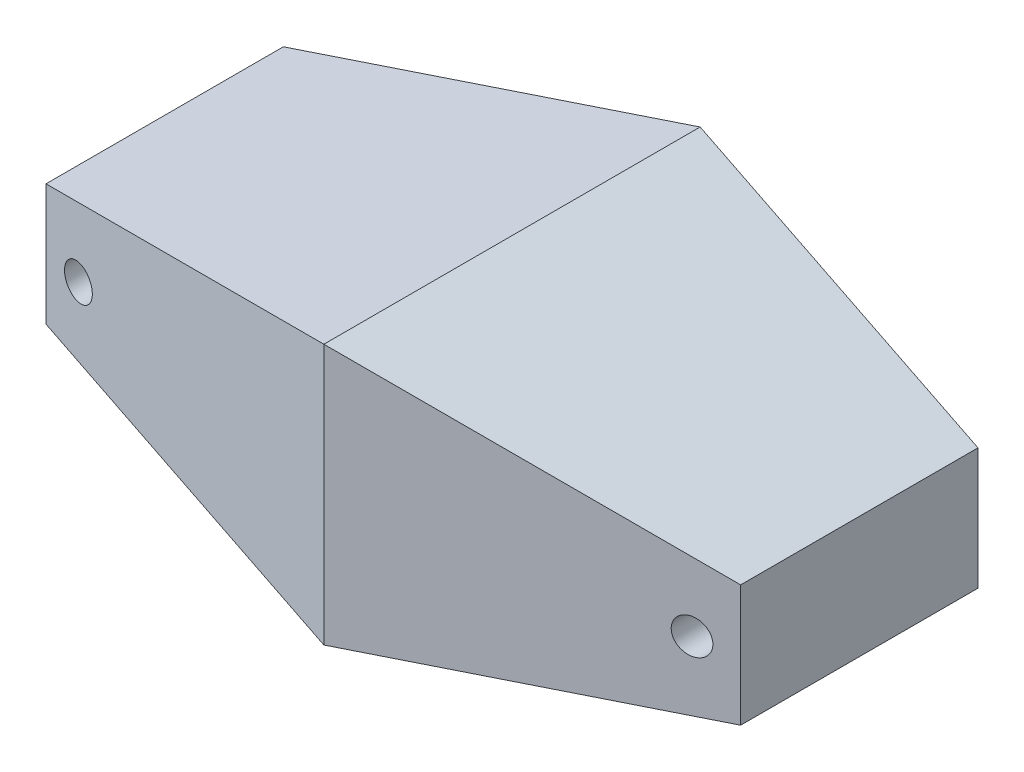
SolidWorks part; units mm, degrees
ref_plane "Front Plane" through (0, 0, 0) normal (0, 0, 1) x (1, 0, 0)
ref_plane "Top Plane" through (0, 0, 0) normal (0, 1, 0) x (1, 0, 0)
ref_plane "Right Plane" through (0, 0, 0) normal (1, 0, 0) x (0, 0, -1)
sketch "Sketch1" plane through (0, 0, 0) normal (0, 0, 1) x (1, 0, 0)
  line L1 (-60, -22.5) -> (60, -22.5)
  line L2 (-60, -22.5) -> (-60, 22.5)
  line L3 (-60, 22.5) -> (60, 22.5)
  line L4 (60, -22.5) -> (60, 22.5)
  line L5 (-60, -22.5) -> (60, 22.5) construction
  line L6 (-60, 22.5) -> (60, -22.5) construction
  point P0 (0, 0)
  dimension "D1" = 120
  dimension "D2" = 45
extrude "Boss-Extrude1" add sketch "Sketch1" along normal blind 65
sketch "Sketch2" plane through (0, 22.5, 0) normal (0, 1, 0) x (1, 0, 0)
  line L0 (0, 0) -> (0, -65) construction
  line L1 (60, -65) -> (-60, -65) construction
  line L2 (0, -32.5) -> (19.388, -32.5) construction
  line L3 (0, 0) -> (-60, -12)
  line L4 (-60, -65) -> (-60, 0) construction
  line L5 (60, 0) -> (-60, 0) construction
  line L6 (0, 0) -> (60, -12)
  line L7 (0, -65) -> (60, -53)
  line L8 (0, -65) -> (-60, -53)
  line L9 (-60, -12) -> (-60, 0)
  line L10 (-60, 0) -> (0, 0)
  line L11 (0, 0) -> (60, 0)
  line L12 (60, 0) -> (60, -12)
  line L13 (60, -53) -> (60, -65)
  line L14 (60, -65) -> (60, 0) construction
  line L15 (60, -65) -> (0, -65)
  line L16 (0, -65) -> (-60, -65)
  line L17 (-60, -65) -> (-60, -53)
  line M5 (60, 0) -> (-60, 0)
  line M6 (-60, 0) -> (-60, -65)
  line M7 (-60, -65) -> (60, -65)
  line M8 (60, -65) -> (60, 0)
  dimension "D1" = 12
extrude "Cut-Extrude1" cut sketch "Sketch2" against normal blind 65 contours L3 M5 M6 | L6 M5 M8 | L7 M7 M8 | L8 M7 M6
sketch "Sketch3" plane through (0, 0, 0) normal (0, 0, 1) x (1, 0, 0)
  line L0 (0, 0) -> (0, 29.0532) construction
  line L1 (0, 0) -> (10.183, 0) construction
  line L2 (0, 22.5) -> (-60, 10.5)
  line L3 (-60, -22.5) -> (-60, 22.5) construction
  line L4 (0, 22.5) -> (-60, 22.5) construction
  line L5 (0, 22.5) -> (60, 10.5)
  line L6 (0, -22.5) -> (60, -10.5)
  line L7 (0, -22.5) -> (-60, -10.5)
  line L8 (-60, 10.5) -> (-60, 22.5)
  line L9 (-60, 22.5) -> (0, 22.5)
  line L10 (0, 22.5) -> (60, 22.5)
  line L11 (60, 22.5) -> (60, 10.5)
  line L12 (60, -10.5) -> (60, -22.5)
  line L13 (60, -22.5) -> (0, -22.5)
  line L14 (-60, -10.5) -> (-60, -22.5)
  line L15 (0, -22.5) -> (-60, -22.5) construction
  line L16 (-60, -22.5) -> (0, -22.5)
  dimension "D1" = 12
extrude "Cut-Extrude2" cut sketch "Sketch3" along normal blind 65 contours L9 L8 L2 | L11 L10 L5 | L13 L12 L6 | L14 L16 L7
sketch "Sketch4" plane through (0, 0, 0) normal (0, 0, 1) x (1, 0, 0)
  line L0 (-60, -10.5) -> (-60, 10.5) construction
  line L1 (0, 0) -> (0, 7.7667) construction
  line L2 (0, 22.5) -> (0, -22.5) construction
  circle A0 centre (-53, 0) radius 3
  circle A1 centre (53, 0) radius 3
  dimension "D1" = 7
extrude "Cut-Extrude3" cut sketch "Sketch4" along normal through all
